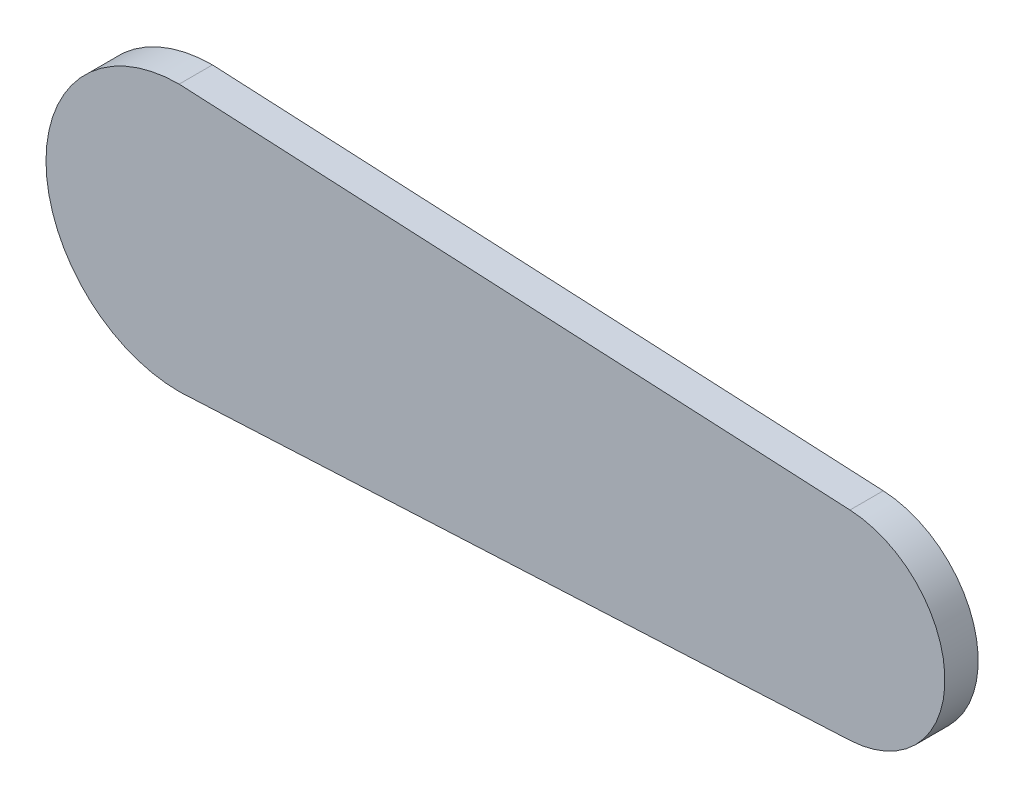
SolidWorks part; units mm, degrees
material "leg"
ref_plane "前视基准面" through (0, 0, 0) normal (0, 0, 1) x (1, 0, 0)
ref_plane "上视基准面" through (0, 0, 0) normal (0, 1, 0) x (1, 0, 0)
ref_plane "右视基准面" through (0, 0, 0) normal (1, 0, 0) x (0, 0, -1)
other "Configuration Table"
sketch "草图1" plane through (0, 0, 0) normal (0, 0, 1) x (1, 0, 0)
  line L0 (0, 0) -> (200, 0)
  line L1 (0, -40) -> (201.4926, -29.9628)
  line L2 (0, 40) -> (201.4926, 29.9628)
  circle A0 centre (0, 0) radius 40
  circle A1 centre (200, 0) radius 30
  dimension "D1" = 80
  dimension "D3" = 60
  dimension "D2" = 200
extrude "凸台-拉伸1" add sketch "草图1" along normal blind 10
